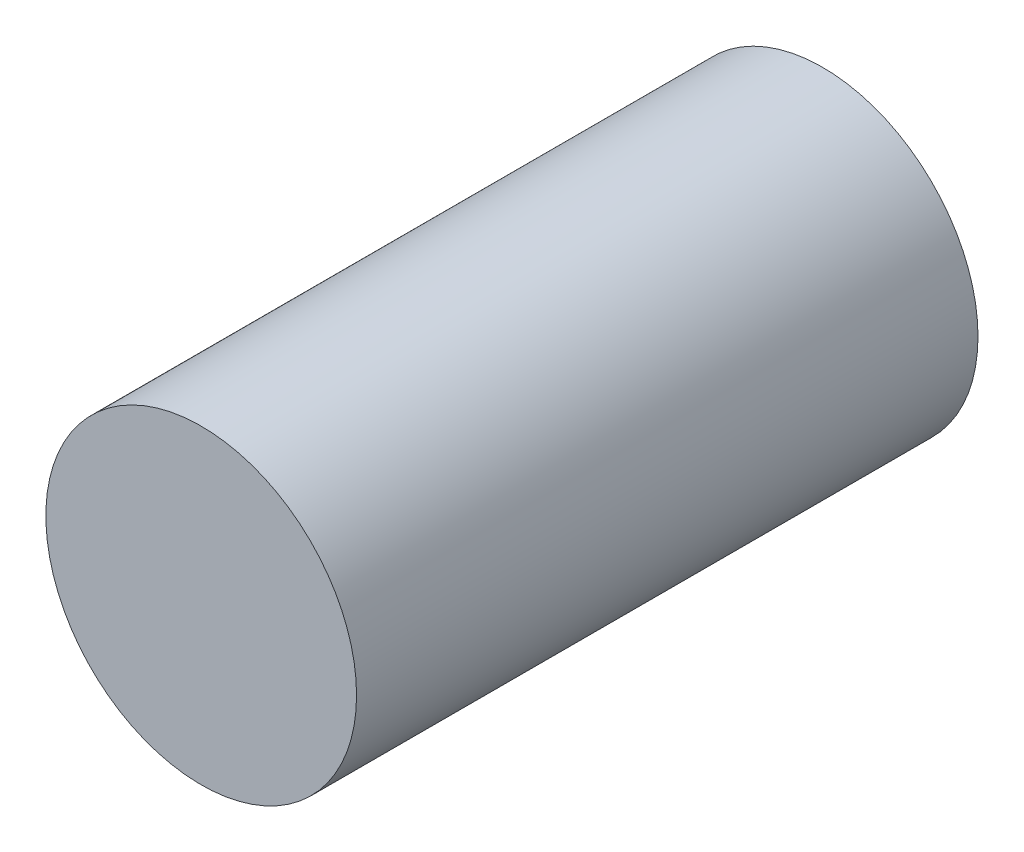
SolidWorks part; units mm, degrees
ref_plane "Front Plane" through (0, 0, 0) normal (0, 0, 1) x (1, 0, 0)
ref_plane "Top Plane" through (0, 0, 0) normal (0, 1, 0) x (1, 0, 0)
ref_plane "Right Plane" through (0, 0, 0) normal (1, 0, 0) x (0, 0, -1)
sketch "Sketch2" plane through (0, 0, 0) normal (0, 0, 1) x (1, 0, 0)
  circle A0 centre (0, 0) radius 2.5
  dimension "D1" = 5
extrude "Boss-Extrude1" add sketch "Sketch2" along normal blind 10
sketch "Sketch3" plane through (0, 0, 0) normal (0, 0, -1) x (-1, 0, 0)
  line L0 (-1.0366, 1.254) -> (1.0366, 1.254)
  arc A0 (-1.0366, 1.254) -> (1.0366, 1.254) centre (0, 0) ccw
  dimension "D1" = 3.254
  dimension "D2" = 1.254
extrude "Cut-Extrude1" cut sketch "Sketch3" against normal blind 9
equation "\"D2@Sketch3\"=2.5-1.5+0.01in"
equation "\"D1@Sketch3\"=3.00mm+0.01in"
